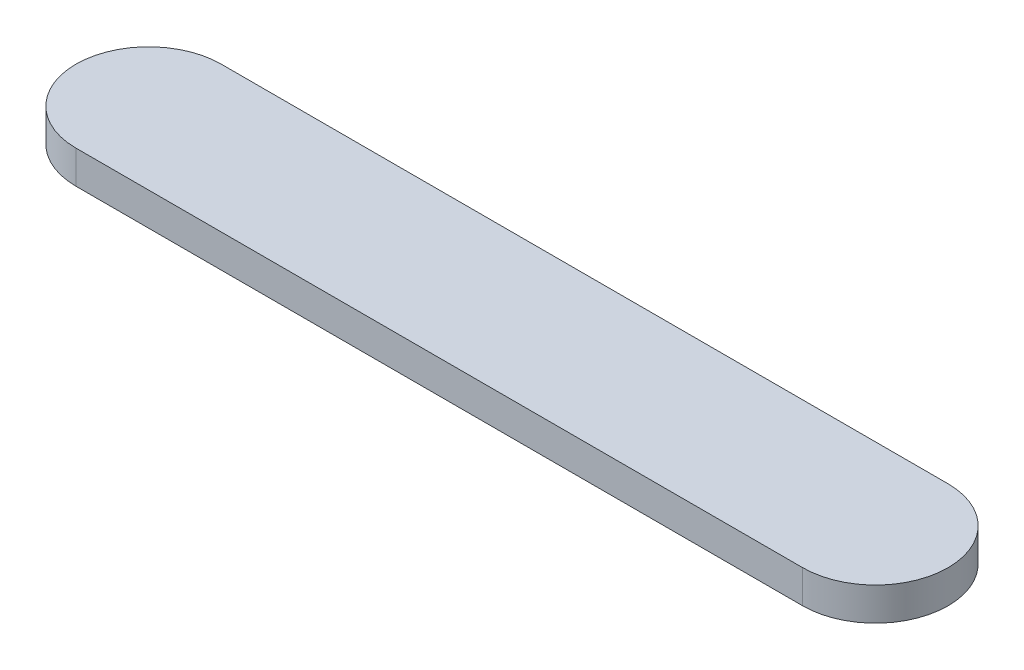
SolidWorks part; units mm, degrees
ref_plane "Plan de face" through (0, 0, 0) normal (0, 0, 1) x (1, 0, 0)
ref_plane "Plan de dessus" through (0, 0, 0) normal (0, 1, 0) x (1, 0, 0)
ref_plane "Plan de droite" through (0, 0, 0) normal (1, 0, 0) x (0, 0, -1)
sketch "Esquisse1" plane through (0, 0, 0) normal (0, 1, 0) x (1, 0, 0)
  line L0 (0, 0) -> (110, 0) construction
  line L1 (0, 11) -> (110, 11)
  line L2 (0, -11) -> (110, -11)
  arc A0 (0, 11) -> (0, -11) centre (0, 0) ccw
  arc A1 (110, -11) -> (110, 11) centre (110, 0) ccw
  point P3 (55, 0)
  dimension "D2" = 11
  dimension "D1" = 110
extrude "Boss.-Extru.1" add sketch "Esquisse1" along normal blind 5
